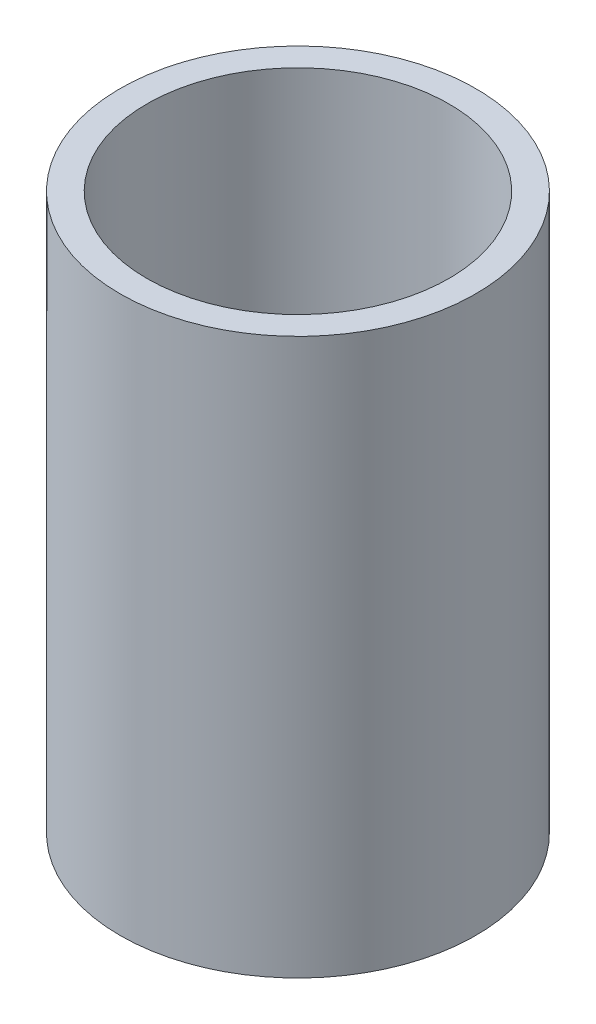
SolidWorks part; units mm, degrees
ref_plane "前视基准面" through (0, 0, 0) normal (0, 0, 1) x (1, 0, 0)
ref_plane "上视基准面" through (0, 0, 0) normal (0, 1, 0) x (1, 0, 0)
ref_plane "右视基准面" through (0, 0, 0) normal (1, 0, 0) x (0, 0, -1)
other "Configuration Table"
sketch "草图1" plane through (0, 0, 0) normal (0, 1, 0) x (1, 0, 0)
  circle A14 centre (0, 0) radius 16
  circle A15 centre (0, 0) radius 13.6
  dimension "D1" = 32
  dimension "D2" = 2.4
extrude "凸台-拉伸1" add sketch "草图1" along normal blind 50
